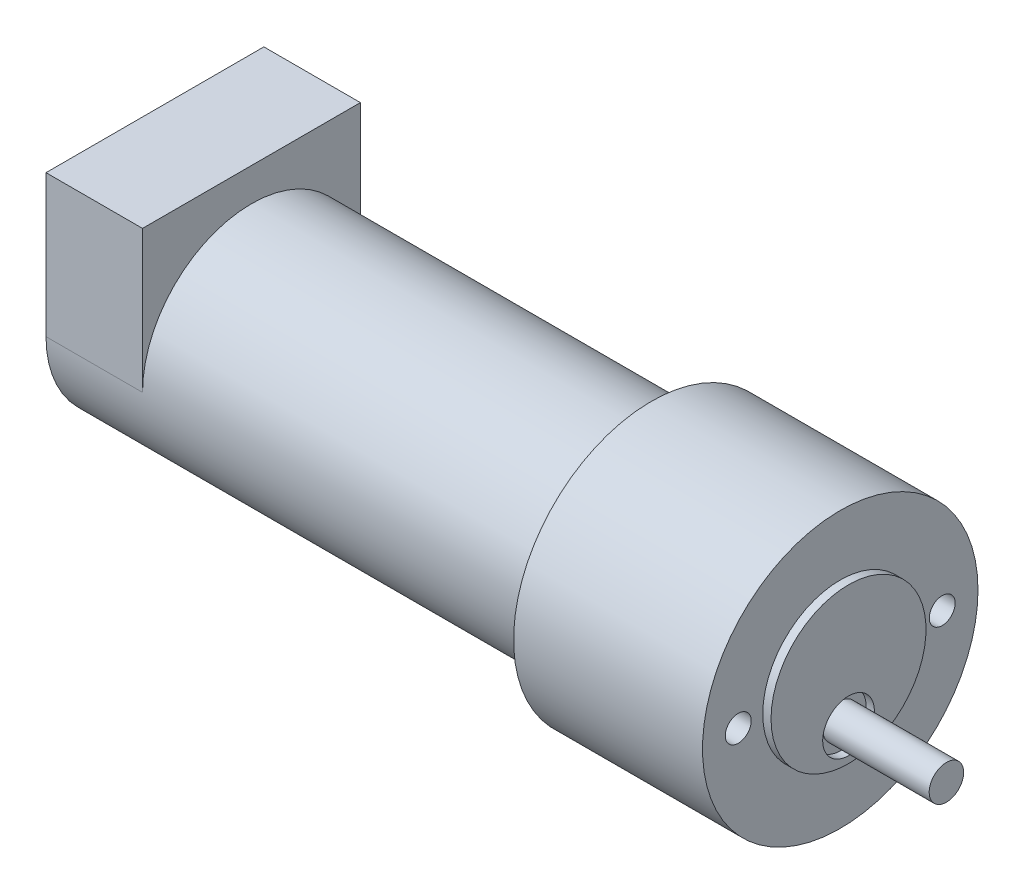
SolidWorks part; units mm, degrees
ref_plane "Front Plane" through (0, 0, 0) normal (0, 0, 1) x (1, 0, 0)
ref_plane "Top Plane" through (0, 0, 0) normal (0, 1, 0) x (1, 0, 0)
ref_plane "Right Plane" through (0, 0, 0) normal (1, 0, 0) x (0, 0, -1)
sketch "Sketch1" plane through (0, 0, 0) normal (1, 0, 0) x (0, 0, -1)
  circle A0 centre (0, 0) radius 20.066
extrude "Boss-Extrude1" add sketch "Sketch1" along normal blind 91.44
sketch "Sketch2" plane through (0, 0, 0) normal (-1, 0, 0) x (0, 0, 1)
  line L0 (-20.066, 0) -> (-20.066, 52.1023) construction
  line L1 (20.066, 0) -> (20.066, 52.8903) construction
  line L2 (-20.066, 26.162) -> (20.066, 26.162)
  line L3 (-20.066, 26.162) -> (-20.066, 0)
  line L4 (20.066, 26.162) -> (20.066, 0)
  circle A0 centre (0, 0) radius 20.066 construction
  arc A1 (20.066, 0) -> (-20.066, 0) centre (0, 0) cw
  dimension "D1" = 26.162
extrude "Boss-Extrude2" add sketch "Sketch2" against normal blind 17.78
sketch "Sketch3" plane through (91.44, 0, 0) normal (1, 0, 0) x (0, 0, -1)
  circle A0 centre (0, 0) radius 25.3746
extrude "Boss-Extrude3" add sketch "Sketch3" along normal blind 34.798
sketch "Sketch4" plane through (126.238, 0, 0) normal (1, 0, 0) x (0, 0, -1)
  circle A0 centre (0, 0) radius 25.4
sketch "Sketch5" plane through (126.238, 0, 0) normal (1, 0, 0) x (0, 0, -1)
  circle A0 centre (0, 0) radius 14.2748
  circle A1 centre (0, -8.2296) radius 4.7625
  dimension "D1" = 8.2296
extrude "Boss-Extrude5" add sketch "Sketch5" along normal blind 1.524
sketch "Sketch6" plane through (126.238, 0, 0) normal (1, 0, 0) x (0, 0, -1)
  circle A0 centre (0, -8.2296) radius 3.175
extrude "Boss-Extrude6" add sketch "Sketch6" along normal blind 19.558
sketch "Sketch7" plane through (126.238, 0, 0) normal (1, 0, 0) x (0, 0, -1)
  line L0 (0, 0) -> (0, 57.8909) construction
  circle A0 centre (18.7833, 0) radius 2.3876
  circle A1 centre (-18.7833, 0) radius 2.3876
  dimension "D1" = 18.7833
extrude "Cut-Extrude1" cut sketch "Sketch7" against normal blind 12.7
